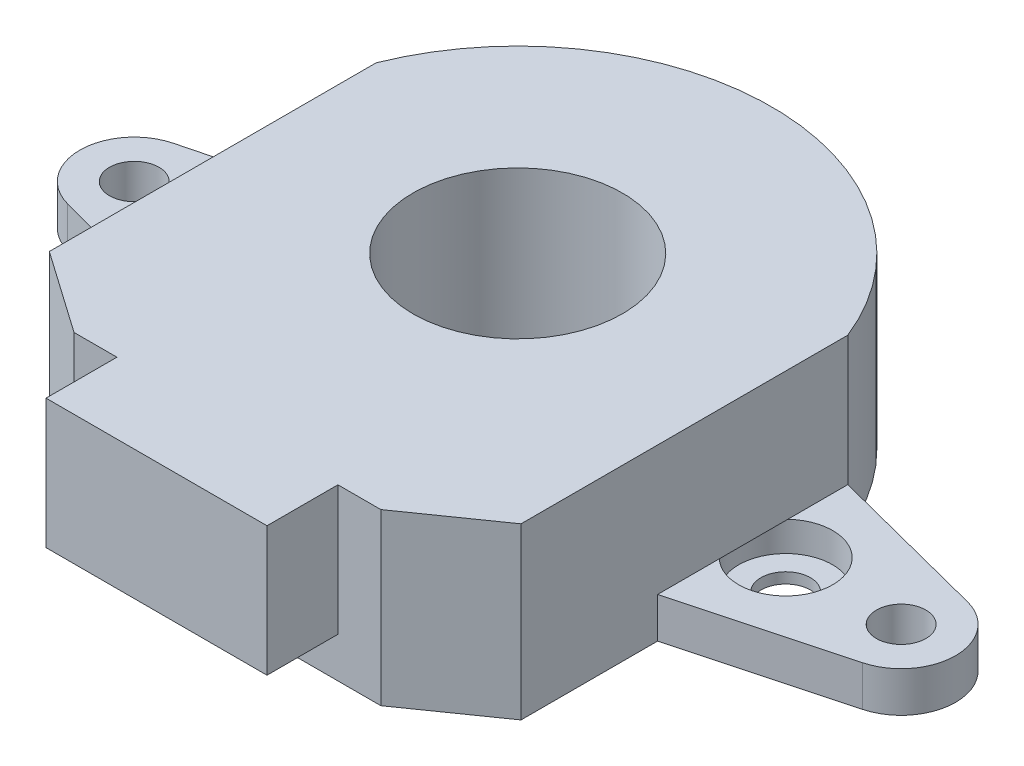
SolidWorks part; units mm, degrees
ref_plane "Front Plane" through (0, 0, 0) normal (0, 0, 1) x (1, 0, 0)
ref_plane "Top Plane" through (0, 0, 0) normal (0, 1, 0) x (1, 0, 0)
ref_plane "Right Plane" through (0, 0, 0) normal (1, 0, 0) x (0, 0, -1)
sketch "Sketch1" plane through (0, 0, 0) normal (0, 1, 0) x (1, 0, 0)
  line L0 (-14.3, -17.6) -> (14.3, -17.6)
  line L1 (-14.3, 5.7158) -> (-14.3, -17.6)
  line L2 (14.3, 5.7158) -> (14.3, -17.6)
  line L3 (0, 15.4) -> (9.5371, 15.4) construction
  line L4 (0, -55) -> (0, 55) construction
  circle A0 centre (0, 0) radius 6.35
  arc A1 (14.3, 5.7158) -> (-14.3, 5.7158) centre (0, 0) ccw
  dimension "D1" = 28.6
  dimension "D2" = 12.7
  dimension "D3" = 33
  dimension "D4" = 30.8
  dimension "D5" = 14.3
extrude "Boss-Extrude1" add sketch "Sketch1" along normal blind 2.45
sketch "Sketch2" plane through (0, 0, 0) normal (0, 1, 0) x (1, 0, 0)
  line L0 (24.074, 3.1955) -> (14.3, 5.7158)
  line L1 (24.1041, -3.1876) -> (14.3, -5.8146)
  line L2 (14.3, -17.6) -> (14.3, 5.7158) construction
  line L3 (-1.3475, 0) -> (1.3475, 0) construction
  line L4 (0, -1.3475) -> (0, 1.3475) construction
  line L5 (23.25, 0) -> (24.074, 3.1955) construction
  line L6 (23.25, 0) -> (24.1041, -3.1876) construction
  line L7 (14.3, 5.7158) -> (14.3, -5.8146)
  circle A1 centre (16.25, 0) radius 1.5
  circle A2 centre (23.25, 0) radius 1.5
  arc A3 (24.074, 3.1955) -> (24.1041, -3.1876) centre (23.25, 0) cw
  dimension "D4" = 3
  dimension "D5" = 3
  dimension "D6" = 16.25
  dimension "D7" = 7
  dimension "D1" = 1.8
  dimension "D2" = 15
extrude "Boss-Extrude2" add sketch "Sketch2" along normal blind 2.45
sketch "Sketch3" plane through (0, 2.45, 0) normal (0, 1, 0) x (1, 0, 0)
  circle A0 centre (16.25, 0) radius 2.85
  dimension "D1" = 5.7
extrude "Cut-Extrude1" cut sketch "Sketch3" against normal blind 1.8
mirror "Mirror1" about plane through (0, 0, 0) normal (1, 0, 0) of "Cut-Extrude1", "Boss-Extrude2"
chamfer "Chamfer1" distance 5 angle 35 2 edges at (-14.3, 1.225, 17.6) (14.3, 1.225, 17.6)
sketch "Sketch5" plane through (0, 2.45, 0) normal (0, 1, 0) x (1, 0, 0)
  line L0 (24.074, 3.1955) -> (14.3, 5.7158) construction
  line L1 (14.3, 5.7158) -> (14.3, -14.099)
  line L2 (14.3, -14.099) -> (14.3, -5.8146) construction
  line L3 (14.3, -14.099) -> (9.3, -17.6)
  line L4 (9.3, -17.6) -> (6.7, -17.6)
  line L5 (-9.3, -17.6) -> (9.3, -17.6) construction
  line L6 (6.7, -17.6) -> (6.7, -21.9)
  line L7 (6.7, -21.9) -> (0, -21.9)
  line L8 (0, -21.9) -> (0, -6.35)
  line L9 (0, -1.3476) -> (0, 1.3476) construction
  line L10 (0, 6.35) -> (0, 15.4)
  arc A0 (0, 15.4) -> (14.3, 5.7158) centre (0, 0) cw
  arc A1 (14.3, 5.7158) -> (-14.3, 5.7158) centre (0, 0) ccw construction
  arc A2 (0, -6.35) -> (0, 6.35) centre (0, 0) ccw
  circle A3 centre (0, 0) radius 6.35 construction
  dimension "D1" = 4.3
  dimension "D2" = 6.7
extrude "Boss-Extrude3" add sketch "Sketch5" along normal blind 7.85
mirror "Mirror2" about plane through (0, 0, 0) normal (1, 0, 0) of "Boss-Extrude3"
